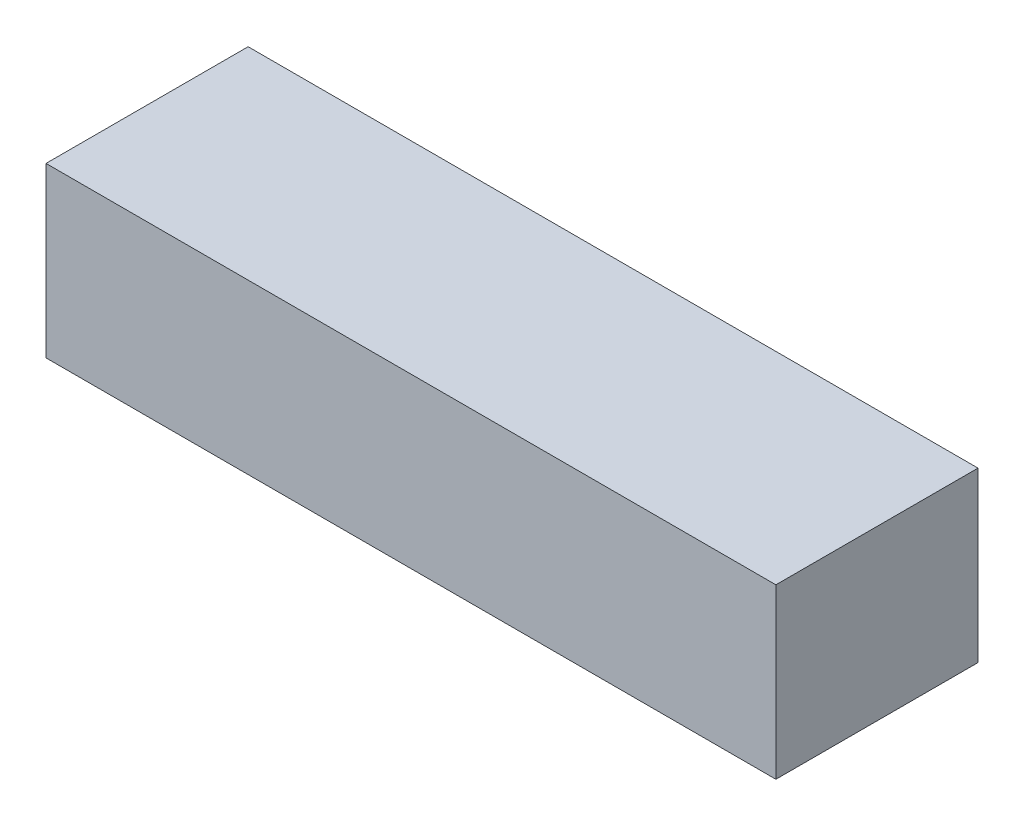
SolidWorks part; units mm, degrees
ref_plane "Alzado" through (0, 0, 0) normal (0, 0, 1) x (1, 0, 0)
ref_plane "Planta" through (0, 0, 0) normal (0, 1, 0) x (1, 0, 0)
ref_plane "Vista lateral" through (0, 0, 0) normal (1, 0, 0) x (0, 0, -1)
sketch "Croquis1" plane through (0, 0, 0) normal (0, 0, 1) x (1, 0, 0)
  line L1 (0, 0) -> (65, 0)
  line L2 (0, 0) -> (0, 15)
  line L3 (0, 15) -> (65, 15)
  line L4 (65, 0) -> (65, 15)
  dimension "D1" = 15
  dimension "D2" = 65
extrude "Saliente-Extruir1" add sketch "Croquis1" against normal blind 18
